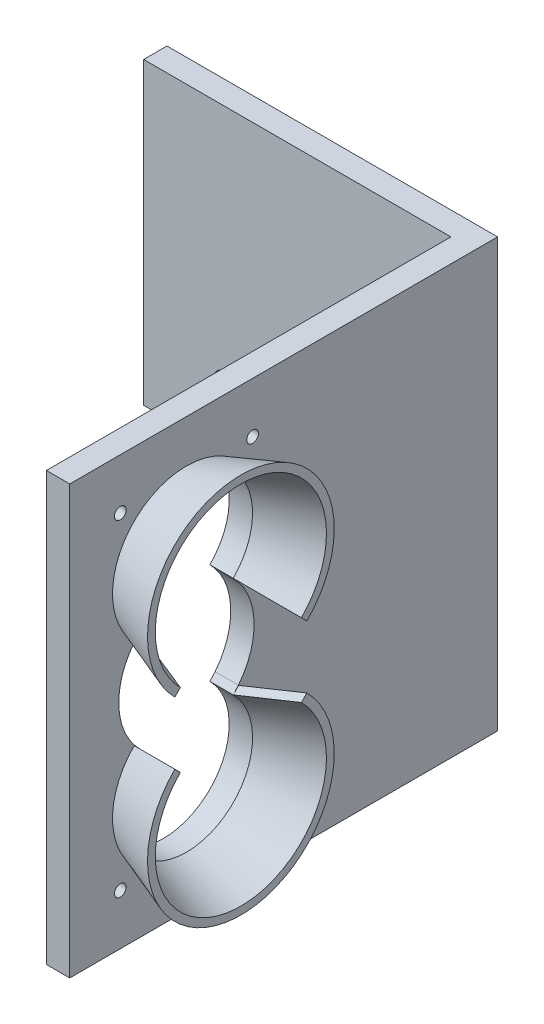
SolidWorks part; units mm, degrees
ref_plane "前视基准面" through (0, 0, 0) normal (0, 0, 1) x (1, 0, 0)
ref_plane "上视基准面" through (0, 0, 0) normal (0, 1, 0) x (1, 0, 0)
ref_plane "右视基准面" through (0, 0, 0) normal (1, 0, 0) x (0, 0, -1)
other "Configuration Table"
sketch "草图1" plane through (0, 0, 0) normal (0, 1, 0) x (1, 0, 0)
  line L0 (-16.6176, 27.2843) -> (25.8824, 27.2843)
  line L1 (25.8824, 27.2843) -> (25.8824, -27.7157)
  line L2 (25.8824, -27.7157) -> (22.8824, -27.7157)
  line L3 (22.8824, -27.7157) -> (22.8824, 24.2843)
  line L4 (22.8824, 24.2843) -> (-16.6176, 24.2843)
  line L5 (-16.6176, 24.2843) -> (-16.6176, 27.2843)
  dimension "D1" = 55
  dimension "D2" = 42.5
  dimension "D3" = 3
  dimension "D4" = 3
extrude "凸台-拉伸1" add sketch "草图1" along normal mid plane 55
ref_plane "基准面1" through (0, 0, -27.2843) normal (0, 0, -1) x (-1, 0, 0)
sketch "草图2" plane through (0, 0, -27.2843) normal (0, 0, -1) x (-1, 0, 0)
  line L0 (4.6176, -3.5) -> (-12.3824, -3.5)
  line L1 (-25.8824, 27.5) -> (-25.8824, -27.5) construction
  line L2 (16.6176, 27.5) -> (16.6176, -27.5) construction
  line L3 (-25.8824, 27.5) -> (16.6176, 27.5) construction
  line L4 (16.6176, -11) -> (-3.3824, -11)
  line L5 (-3.3824, -11) -> (-3.3824, -27.5)
  line L6 (-25.8824, -27.5) -> (16.6176, -27.5) construction
  line L7 (-3.3824, -27.5) -> (16.6176, -27.5)
  line L8 (16.6176, -27.5) -> (16.6176, -11)
  circle A2 centre (6.1176, -3.5) radius 1.5
  circle A3 centre (-13.8824, -3.5) radius 1.5
  dimension "D3" = 3
  dimension "D4" = 3
  dimension "D1" = 31
  dimension "D2" = 31
  dimension "D5" = 10.5
  dimension "D6" = 12
  dimension "D7" = 7.5
  dimension "D8" = 20
ref_plane "基准面2" through (25.8824, 0, 0) normal (1, 0, 0) x (0, 0, -1)
sketch "草图3" plane through (25.8824, 0, 0) normal (1, 0, 0) x (0, 0, -1)
  line L0 (-27.7157, 27.5) -> (-27.7157, -27.5) construction
  line L1 (-22.7157, 22.5) -> (-2.7157, 22.5)
  line L2 (-22.7157, 22.5) -> (-22.7157, -22.5)
  line L3 (-22.7157, -22.5) -> (-2.7157, -22.5)
  line L4 (-2.7157, 22.5) -> (-2.7157, -22.5)
  line L5 (-22.7157, 22.5) -> (-2.7157, -22.5) construction
  line L6 (-22.7157, -22.5) -> (-2.7157, 22.5) construction
  line L7 (-12.7157, 22.5) -> (-12.7157, 22)
  line L8 (-12.7157, 12.5) -> (-6.7053, 6.4896)
  line L9 (-12.7157, 12.5) -> (-18.7261, 6.4896)
  line L10 (-12.7157, -12.5) -> (-18.7261, -6.4896)
  line L11 (-12.7157, -12.5) -> (-6.7053, -6.4896)
  line L12 (-12.7157, -22) -> (-12.7157, -22.5)
  line L13 (-12.7157, -4) -> (-12.7157, -21)
  line L14 (-12.7157, 3) -> (-12.7157, -3)
  line L15 (-12.7157, 21) -> (-12.7157, 4)
  line L16 (-22.7157, 0) -> (-2.7157, 0)
  line L17 (-18.7261, 6.4896) -> (-19.3945, 5.744)
  line L18 (-6.7053, 6.4896) -> (-6.0369, 5.744)
  line L19 (-6.7053, -6.4896) -> (-6.0369, -5.744)
  line L20 (-18.7261, -6.4896) -> (-19.3945, -5.744)
  circle A0 centre (-12.7157, 12.5) radius 8.5
  circle A1 centre (-12.7157, -12.5) radius 8.5
  arc A2 (-6.0369, 5.744) -> (-6.0369, -5.744) centre (-13.1949, 0) cw
  arc A3 (-19.3945, 5.744) -> (-19.3945, -5.744) centre (-12.2365, 0) ccw
  circle A4 centre (-12.7157, 12.5) radius 9.5
  circle A5 centre (-12.7157, -12.5) radius 9.5
  circle A6 centre (-4.2157, -21) radius 0.75
  circle A7 centre (-21.2157, -21) radius 0.75
  circle A8 centre (-4.2157, 21) radius 0.75
  circle A9 centre (-21.2157, 21) radius 0.75
  point P0 (0, 0)
  dimension "D6" = 17
  dimension "D7" = 17
  dimension "D8" = 19
  dimension "D9" = 19
  dimension "D11" = 1.5
  dimension "D1" = 45
  dimension "D2" = 20
  dimension "D3" = 5
  dimension "D4" = 10
  dimension "D5" = 10
  dimension "D10" = 1.5
  dimension "D12" = 1.5
extrude "切除-拉伸3" cut sketch "草图3" against normal blind 3 contours L8 A0 L15 | L15 A0 L8 | L9 A0 L15 | L15 A0 L9 | A4 L14 L16 A2 | A5 A2 L16 L14 | A4 A3 L16 L14 | A5 L14 L16 A3 | L13 A1 L11 | L11 A1 L13 | L13 A1 L10 | L10 A1 L13 | A7 | A6 | A9 | A8 | L19 A5 L20 A1 | L17 A4 L18 A0
ref_plane "基准面3" through (32.8824, 0, 0) normal (1, 0, 0) x (0, 0, -1)
sketch "草图4" plane through (32.8824, 0, 0) normal (1, 0, 0) x (0, 0, -1)
  circle A0 centre (-12.7157, 12.5) radius 12
  circle A1 centre (-12.7157, 12.5) radius 11
ref_plane "基准面4" through (0, 0, 12.7157) normal (0, 0, 1) x (0, -1, 0)
sketch "草图5" plane through (0, 0, 12.7157) normal (0, 0, 1) x (0, -1, 0)
  line L0 (-3, 25.8824) -> (-22, 25.8824) construction
  line L1 (-0.5, 32.8824) -> (-24.5, 32.8824) construction
  line L2 (-3, 25.8824) -> (-22, 25.8824)
  line L3 (-0.5, 32.8824) -> (-24.5, 32.8824)
  line L4 (-3, 25.8824) -> (-22, 25.8824)
  line L5 (-22, 25.8824) -> (-24.5, 32.8824)
  line L6 (-22, 25.8824) -> (-21, 25.8824)
  line L7 (-21, 25.8824) -> (-23.5, 32.8824)
  line L8 (-23.5, 32.8824) -> (-24.5, 32.8824)
  line L9 (-12.5, 32.8824) -> (-12.5, 25.8824)
  point P4 (-12.5, 32.8824)
  dimension "D1" = 1
revolve "旋转1" add sketch "草图5" angle 135 about L9
mirror "镜向1" about plane through (0, 0, 0) normal (0, 1, 0) of "旋转1"
mirror "镜向2" about plane through (0, 0, 12.7157) normal (0, 0, 1) of "旋转1"
mirror "镜向3" about plane through (0, 0, 12.7157) normal (0, 0, 1) of "镜向1"
extrude "切除-拉伸4" cut sketch "草图2" against normal blind 3 contours A2 | A3 | L7 L8 L4 L5
